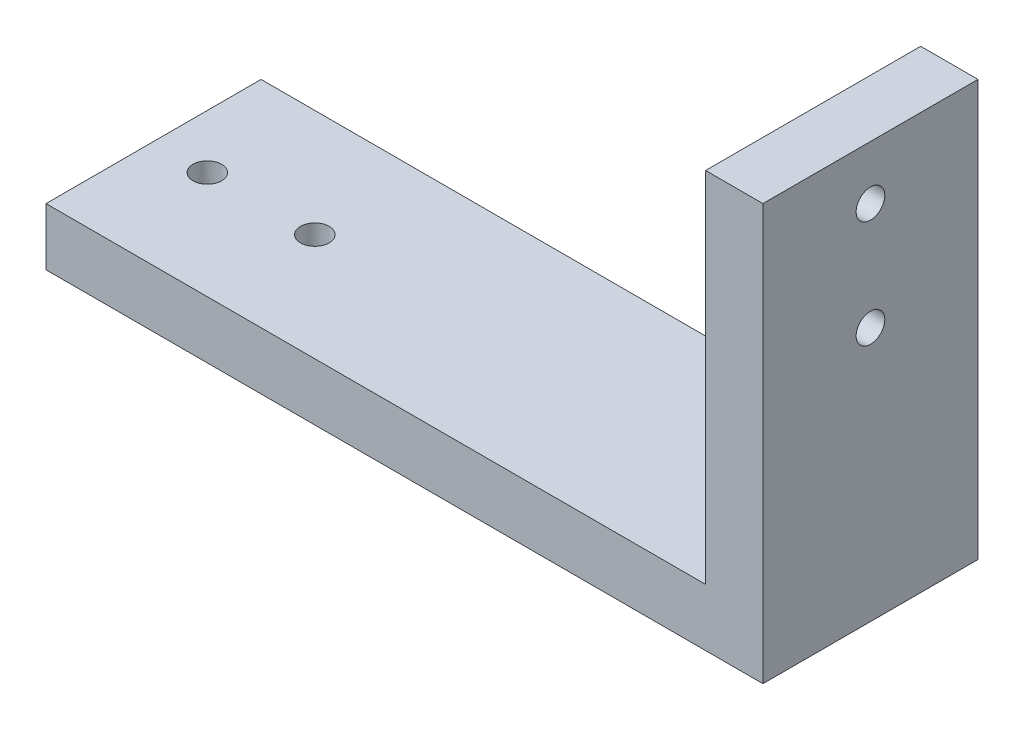
SolidWorks part; units mm, degrees
ref_plane "Front Plane" through (0, 0, 0) normal (0, 0, 1) x (1, 0, 0)
ref_plane "Top Plane" through (0, 0, 0) normal (0, 1, 0) x (1, 0, 0)
ref_plane "Right Plane" through (0, 0, 0) normal (1, 0, 0) x (0, 0, -1)
sketch "Sketch1" plane through (0, 0, 0) normal (0, 1, 0) x (1, 0, 0)
  line L0 (-42.5, 0) -> (-27.5, 0) construction
  line L1 (-50, 15) -> (50, 15)
  line L2 (-50, 15) -> (-50, -15)
  line L3 (-50, -15) -> (50, -15)
  line L4 (50, 15) -> (50, -15)
  line L5 (-50, 15) -> (50, -15) construction
  line L6 (-50, -15) -> (50, 15) construction
  circle A0 centre (-42.5, 0) radius 2
  circle A1 centre (-27.5, 0) radius 2
  point P0 (0, 0)
  dimension "D3" = 7.5
  dimension "D4" = 15
  dimension "D5" = 4
  dimension "D6" = 4
  dimension "D7" = 15
  dimension "D1" = 100
  dimension "D2" = 30
extrude "Boss-Extrude1" add sketch "Sketch1" along normal blind 8
sketch "Sketch2" plane through (0, 8, 0) normal (0, 1, 0) x (1, 0, 0)
  line L0 (-50, -15) -> (50, -15) construction
  line L1 (50, 15) -> (42, 15)
  line L2 (50, 15) -> (50, -15)
  line L3 (50, -15) -> (42, -15)
  line L4 (42, 15) -> (42, -15)
  dimension "D1" = 8
extrude "Boss-Extrude2" add sketch "Sketch2" along normal blind 50
sketch "Sketch3" plane through (50, 0, 0) normal (1, 0, 0) x (0, 0, -1)
  line L0 (0, 50.5) -> (0, 35.5) construction
  line L1 (-15, 58) -> (15, 58) construction
  line L2 (-15, 58) -> (-15, 0) construction
  circle A0 centre (0, 50.5) radius 2
  circle A1 centre (0, 35.5) radius 2
  dimension "D1" = 4
  dimension "D2" = 4
  dimension "D4" = 7.5
  dimension "D3" = 15
  dimension "D5" = 15
extrude "Cut-Extrude1" cut sketch "Sketch3" against normal blind 50
